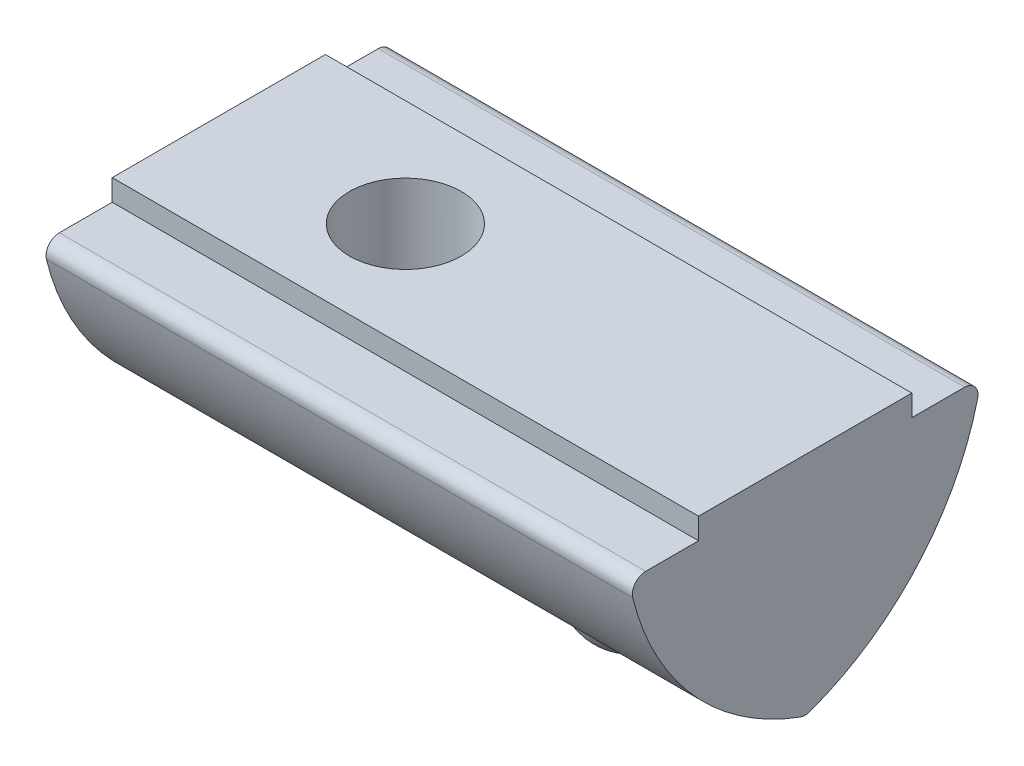
SolidWorks part; units mm, degrees
ref_plane "Płaszczyzna przednia" through (0, 0, 0) normal (0, 0, 1) x (1, 0, 0)
ref_plane "Płaszczyzna górna" through (0, 0, 0) normal (0, 1, 0) x (1, 0, 0)
ref_plane "Płaszczyzna prawa" through (0, 0, 0) normal (1, 0, 0) x (0, 0, -1)
sketch "Szkic1" plane through (0, 0, 0) normal (1, 0, 0) x (0, 0, -1)
  line L0 (-4, 0) -> (4, 0)
  line L1 (4, 0) -> (4, -0.8)
  line L2 (4, -0.8) -> (6.6, -0.8)
  line L3 (0, 0) -> (0, -50000) construction
  line L4 (-4, -0.8) -> (-6.6, -0.8)
  line L5 (-4, 0) -> (-4, -0.8)
  arc A0 (-6.6, -0.8) -> (0, -8.5) centre (3.244, 0.9592) ccw
  arc A1 (6.6, -0.8) -> (0, -8.5) centre (-3.244, 0.9592) cw
  point P7 (0, 0)
  dimension "D5" = 10
  dimension "D1" = 8
  dimension "D2" = 0.8
  dimension "D3" = 13.2
  dimension "D4" = 8.5
extrude "Dodanie-wyciągnięcie1" add sketch "Szkic1" along normal mid plane 22 contours A0 A1 L2 L1 L0 L5 L4
fillet "Zaokrąglenie1" radius 0.5 3 edges at (0, -0.8, -6.6) (0, -8.5, 0) (0, -0.8, 6.6)
hole_wizard "Otwór gwintowany M51" positions "Szkic2" profile "Szkic3" tap size "M5" standard "ISO" end condition through all
sketch "Szkic2" plane through (0, 0, 0) normal (0, 1, 0) x (1, 0, 0)
  line L0 (-11, -4) -> (-11, 4) construction
  point P0 (-4, 0)
  point P5 (0, 0)
  dimension "D1" = 7
sketch "Szkic3" plane through (-4, 0, 0) normal (1, 0, 0) x (0, 0, 1)
  line L0 (0, 0) -> (0, 8.4698)
  line L1 (0, 8.4698) -> (2.1, 8.4698)
  line L2 (2.1, 8.4698) -> (2.1, 0)
  line L5 (2.1, 0) -> (0, 0)
  line L11 (0, -6.35) -> (0, 107.95) construction
  dimension "Średnica otworu gwintowanego na wylot" = 4.2
  dimension "Głębokość otworu gwintowanego na wylot" = 8.4698
cosmetic thread "Gwint otworu1" parameters "D2"=5
ref_plane "Płaszczyzna1" through (4.5, 0, 0) normal (-1, 0, 0) x (0, 0, 1)
sketch "Szkic4" plane through (4.5, 0, 0) normal (-1, 0, 0) x (0, 0, 1)
  line L0 (-3.5599, -9.3) -> (49996.4401, -9.3) construction
  line L1 (4, 0) -> (-4, 0) construction
  line L2 (0, -7.3) -> (0, 49992.7) construction
  line L3 (0, -5.3) -> (0, -9.3)
  arc A0 (0, -9.3) -> (0, -5.3) centre (0, -7.3) ccw
  dimension "D2" = 4
  dimension "D1" = 9.3
revolve "Obrót1" add sketch "Szkic4" angle 360 about L3
